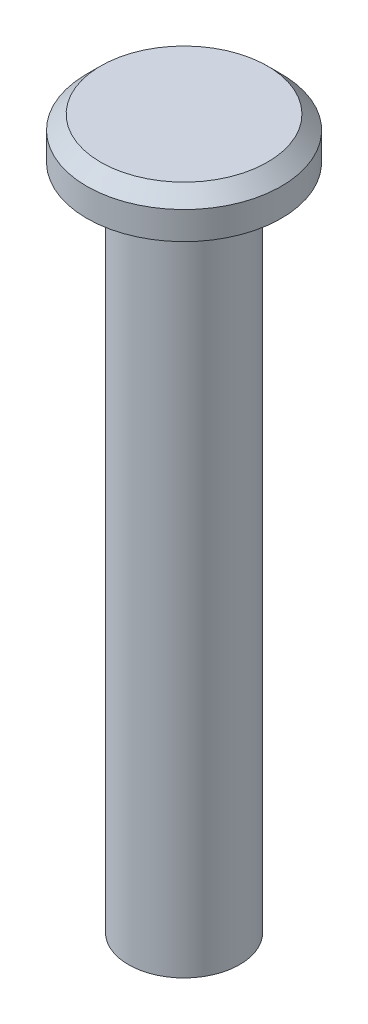
SolidWorks part; units mm, degrees
ref_plane "Front Plane" through (0, 0, 0) normal (0, 0, 1) x (1, 0, 0)
ref_plane "Top Plane" through (0, 0, 0) normal (0, 1, 0) x (1, 0, 0)
ref_plane "Right Plane" through (0, 0, 0) normal (1, 0, 0) x (0, 0, -1)
sketch "Sketch2" plane through (0, 0, 0) normal (0, 1, 0) x (1, 0, 0)
  circle A0 centre (0, 0) radius 7
  dimension "D1" = 14
extrude "Boss-Extrude1" add sketch "Sketch2" along normal blind 3
sketch "Sketch3" plane through (0, 0, 0) normal (0, -1, 0) x (1, 0, 0)
  circle A0 centre (0, 0) radius 4
  dimension "D1" = 8
extrude "Boss-Extrude2" add sketch "Sketch3" along normal blind 48
cosmetic thread "Cosmetic Thread1"
chamfer "Chamfer1" distance 1 angle 45 1 edges at (0, 3, 7)
